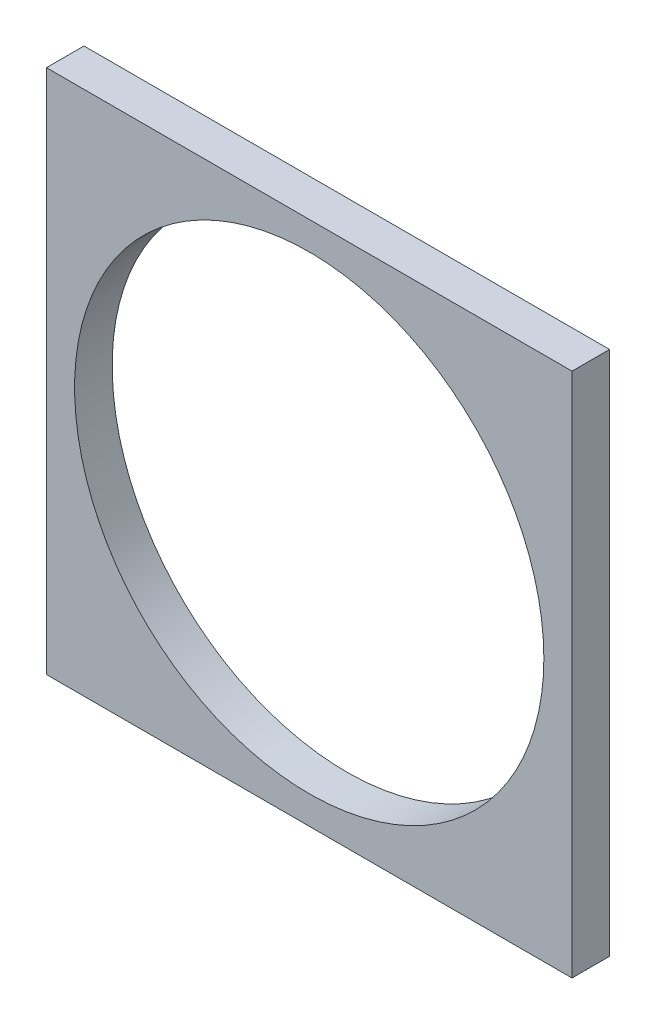
SolidWorks part; units mm, degrees
ref_plane "Front Plane" through (0, 0, 0) normal (0, 0, 1) x (1, 0, 0)
ref_plane "Top Plane" through (0, 0, 0) normal (0, 1, 0) x (1, 0, 0)
ref_plane "Right Plane" through (0, 0, 0) normal (1, 0, 0) x (0, 0, -1)
sketch "Sketch1" plane through (0, 0, 0) normal (0, 0, 1) x (1, 0, 0)
  line L1 (-7, 7) -> (7, 7)
  line L2 (-7, 7) -> (-7, -7)
  line L3 (-7, -7) -> (7, -7)
  line L4 (7, 7) -> (7, -7)
  line L5 (-7, 7) -> (7, -7) construction
  line L6 (-7, -7) -> (7, 7) construction
  circle A0 centre (0, 0) radius 6.25
  point P0 (0, 0)
  dimension "D3" = 12.5
  dimension "D1" = 14
  dimension "D2" = 14
extrude "Boss-Extrude1" add sketch "Sketch1" along normal blind 1
